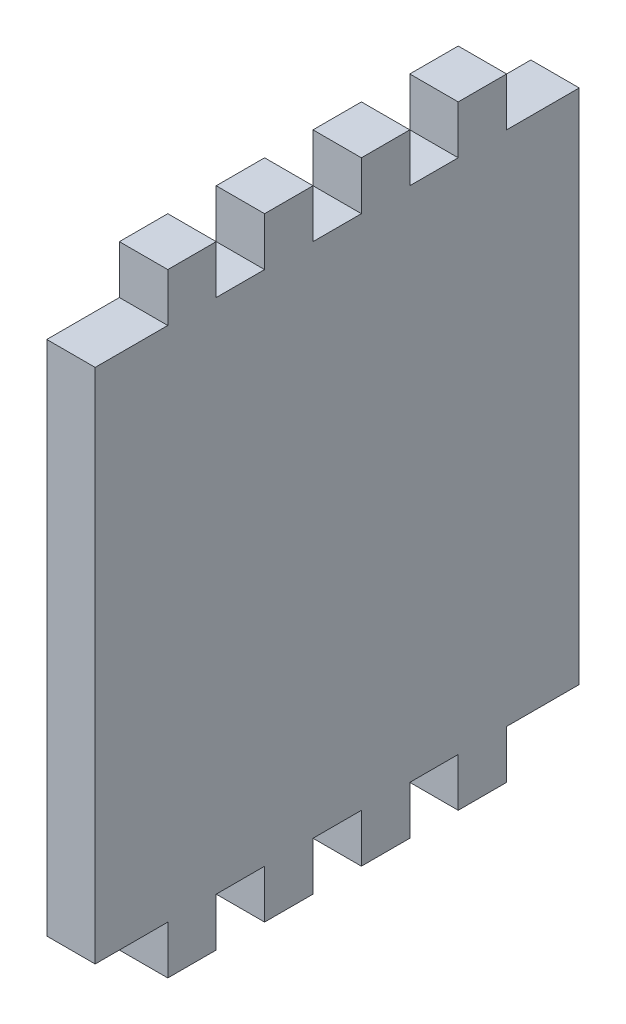
SolidWorks part; units mm, degrees
ref_plane "Front Plane" through (0, 0, 0) normal (0, 0, 1) x (1, 0, 0)
ref_plane "Top Plane" through (0, 0, 0) normal (0, 1, 0) x (1, 0, 0)
ref_plane "Right Plane" through (0, 0, 0) normal (1, 0, 0) x (0, 0, -1)
sketch "Sketch1" plane through (0, 0, 0) normal (1, 0, 0) x (0, 0, -1)
  line L1 (-20.2237, 14.0844) -> (30.5763, 14.0844)
  line L2 (-20.2237, 14.0844) -> (-20.2237, -40.1421)
  line L3 (-20.2237, -40.1421) -> (30.5763, -40.1421)
  line L4 (30.5763, 14.0844) -> (30.5763, -40.1421)
  dimension "D1" = 50.8
  dimension "D2" = 54.2265
extrude "Boss-Extrude1" add sketch "Sketch1" along normal blind 5.08
sketch "Sketch2" plane through (5.08, 0, 0) normal (1, 0, 0) x (0, 0, -1)
  line L0 (5.1763, 14.0844) -> (5.1763, -40.1421) construction
  line L1 (30.5763, 14.0844) -> (-20.2237, 14.0844) construction
  line L2 (-20.2237, -40.1421) -> (30.5763, -40.1421) construction
  line L3 (-20.2237, -13.0289) -> (30.5763, -13.0289) construction
  line L4 (-20.2237, 14.0844) -> (-20.2237, -40.1421) construction
  line L5 (30.5763, -40.1421) -> (30.5763, 14.0844) construction
  line L6 (-12.6037, 14.0844) -> (-12.6037, 19.1644)
  line L7 (7.7163, 14.0844) -> (12.7963, 14.0844)
  line L8 (7.7163, 14.0844) -> (7.7163, 19.1644)
  line L9 (7.7163, 19.1644) -> (12.7963, 19.1644)
  line L10 (12.7963, 14.0844) -> (12.7963, 19.1644)
  line L11 (17.8763, 14.0844) -> (22.9563, 14.0844)
  line L12 (17.8763, 14.0844) -> (17.8763, 19.1644)
  line L13 (17.8763, 19.1644) -> (22.9563, 19.1644)
  line L14 (22.9563, 14.0844) -> (22.9563, 19.1644)
  line L15 (-7.5237, 19.1644) -> (-12.6037, 19.1644)
  line L16 (-7.5237, 14.0844) -> (-7.5237, 19.1644)
  line L17 (-7.5237, 14.0844) -> (-12.6037, 14.0844)
  line L18 (-2.4437, 14.0844) -> (-2.4437, 19.1644)
  line L19 (2.6363, 19.1644) -> (-2.4437, 19.1644)
  line L20 (2.6363, 14.0844) -> (2.6363, 19.1644)
  line L21 (2.6363, 14.0844) -> (-2.4437, 14.0844)
  line L22 (2.6363, -40.1421) -> (-2.4437, -40.1421)
  line L23 (2.6363, -40.1421) -> (2.6363, -45.2221)
  line L24 (2.6363, -45.2221) -> (-2.4437, -45.2221)
  line L25 (-2.4437, -40.1421) -> (-2.4437, -45.2221)
  line L26 (-7.5237, -40.1421) -> (-12.6037, -40.1421)
  line L27 (-7.5237, -40.1421) -> (-7.5237, -45.2221)
  line L28 (-7.5237, -45.2221) -> (-12.6037, -45.2221)
  line L29 (22.9563, -40.1421) -> (22.9563, -45.2221)
  line L30 (17.8763, -45.2221) -> (22.9563, -45.2221)
  line L31 (17.8763, -40.1421) -> (17.8763, -45.2221)
  line L32 (17.8763, -40.1421) -> (22.9563, -40.1421)
  line L33 (12.7963, -40.1421) -> (12.7963, -45.2221)
  line L34 (7.7163, -45.2221) -> (12.7963, -45.2221)
  line L35 (7.7163, -40.1421) -> (7.7163, -45.2221)
  line L36 (7.7163, -40.1421) -> (12.7963, -40.1421)
  line L37 (-12.6037, -40.1421) -> (-12.6037, -45.2221)
  dimension "D1" = 5.08
  dimension "D2" = 5.08
  dimension "D3" = 5.08
  dimension "D4" = 5.08
  dimension "D5" = 2.54
  dimension "D6" = 5.08
extrude "Boss-Extrude2" add sketch "Sketch2" against normal blind 5.08
